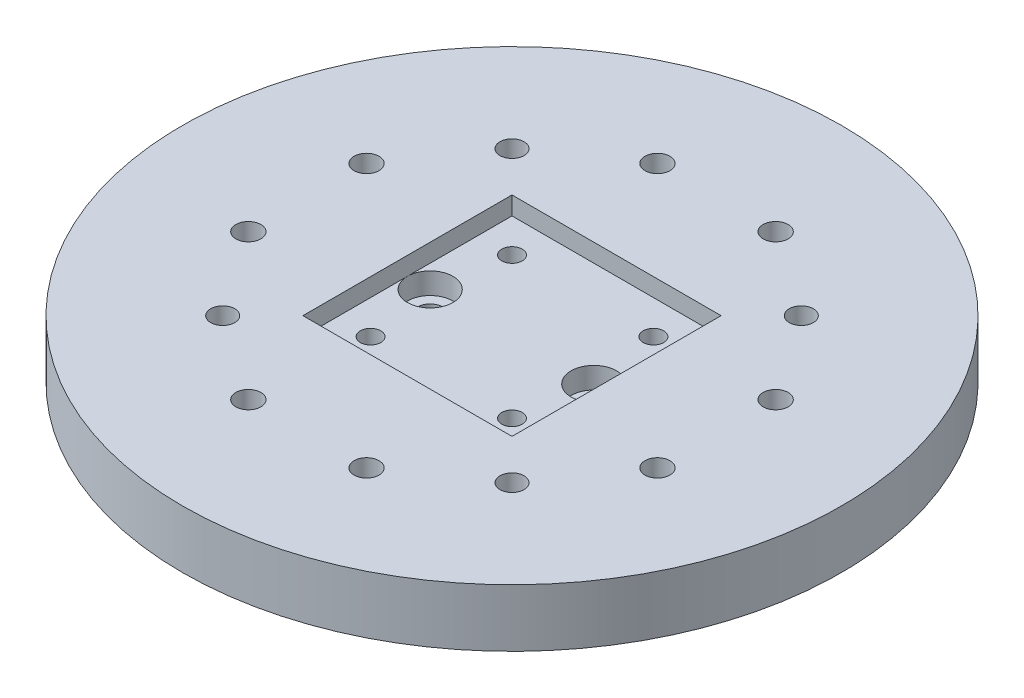
SolidWorks part; units mm, degrees
ref_plane "Front Plane" through (0, 0, 0) normal (0, 0, 1) x (1, 0, 0)
ref_plane "Top Plane" through (0, 0, 0) normal (0, 1, 0) x (1, 0, 0)
ref_plane "Right Plane" through (0, 0, 0) normal (1, 0, 0) x (0, 0, -1)
sketch "Sketch1" plane through (0, 0, 0) normal (0, 1, 0) x (1, 0, 0)
  circle A0 centre (0, 0) radius 72.5
  dimension "D1" = 145
extrude "Boss-Extrude1" add sketch "Sketch1" along normal blind 12.7
sketch "Sketch2" plane through (0, 0, 0) normal (0, -1, 0) x (1, 0, 0)
  line L0 (0, 0) -> (31.8198, 31.8198) construction
  line L1 (0, 72.5) -> (0, -72.5) construction
  line L2 (-31.8198, -31.8198) -> (0, 0) construction
  line L3 (-31.8198, 31.8198) -> (31.8198, -31.8198) construction
  circle A0 centre (0, 0) radius 72.5 construction
  circle A1 centre (31.8198, 31.8198) radius 2.65
  circle A2 centre (31.8198, -31.8198) radius 2.65
  circle A3 centre (-31.8198, -31.8198) radius 2.65
  circle A4 centre (-31.8198, 31.8198) radius 2.65
  dimension "D3" = 5.3
  dimension "D1" = 45
  dimension "D2" = 45
  dimension "D4" = 4
extrude "Cut-Extrude1" cut sketch "Sketch2" against normal through all
sketch "Sketch3" plane through (0, 0, 0) normal (0, -1, 0) x (1, 0, 0)
  circle A0 centre (-31.8198, 31.8198) radius 5
  circle A1 centre (31.8198, 31.8198) radius 5
  circle A2 centre (31.8198, -31.8198) radius 5
  circle A3 centre (-31.8198, -31.8198) radius 5
  circle A4 centre (31.8198, -31.8198) radius 2.65 construction
  dimension "D1" = 10
  dimension "D2" = 4
extrude "Cut-Extrude2" cut sketch "Sketch3" against normal blind 5
sketch "Sketch4" plane through (0, 0, 0) normal (0, -1, 0) x (1, 0, 0)
  line L0 (0, 0) -> (0, 45) construction
  line L1 (0, 0) -> (0, -45) construction
  circle A0 centre (13, 45) radius 2.75
  circle A1 centre (-13, 45) radius 2.75
  circle A2 centre (45, -13) radius 2.75
  circle A3 centre (45, 13) radius 2.75
  circle A4 centre (-13, -45) radius 2.75
  circle A5 centre (13, -45) radius 2.75
  circle A6 centre (-45, 13) radius 2.75
  circle A7 centre (-45, -13) radius 2.75
  dimension "D2" = 5.5
  dimension "D1" = 45
  dimension "D3" = 13
  dimension "D4" = 4
extrude "Cut-Extrude3" cut sketch "Sketch4" against normal through all
sketch "Sketch7" plane through (0, 12.7, 0) normal (0, 1, 0) x (1, 0, 0)
  line L1 (-23, 23) -> (23, 23)
  line L2 (-23, 23) -> (-23, -23)
  line L3 (-23, -23) -> (23, -23)
  line L4 (23, 23) -> (23, -23)
  line L5 (-23, 23) -> (23, -23) construction
  line L6 (-23, -23) -> (23, 23) construction
  point P0 (0, 0)
  dimension "D1" = 46
extrude "Cut-Extrude6" cut sketch "Sketch7" against normal blind 4
sketch "Sketch8" plane through (0, 8.7, 0) normal (0, 1, 0) x (1, 0, 0)
  line L0 (0, 23) -> (0, -23) construction
  line L1 (23, 23) -> (-23, 23) construction
  line L2 (-23, -23) -> (23, -23) construction
  line L3 (-23, 0) -> (23, 0) construction
  line L4 (-23, 23) -> (-23, -23) construction
  line L5 (23, -23) -> (23, 23) construction
  line L6 (0, 0) -> (15.5563, 15.5563) construction
  circle A0 centre (15.5563, 15.5563) radius 2.25
  circle A1 centre (-15.5563, 15.5563) radius 2.25
  circle A2 centre (15.5563, -15.5563) radius 2.25
  circle A3 centre (-15.5563, -15.5563) radius 2.25
  dimension "D3" = 4.5
  dimension "D1" = 22
  dimension "D2" = 45
extrude "Cut-Extrude7" cut sketch "Sketch8" against normal through all
sketch "Sketch9" plane through (0, 0, 0) normal (0, -1, 0) x (1, 0, 0)
  line L0 (0, -6.985) -> (0, 6.985) construction
  circle A0 centre (18, 0) radius 2.75
  circle A1 centre (-18, 0) radius 2.75
  dimension "D1" = 5.5
  dimension "D2" = 18
extrude "Cut-Extrude8" cut sketch "Sketch9" against normal through all
sketch "Sketch10" plane through (0, 8.7, 0) normal (0, 1, 0) x (1, 0, 0)
  line L0 (0, -6.985) -> (0, 6.985) construction
  circle A0 centre (-18, 0) radius 5
  circle A1 centre (18, 0) radius 5
  dimension "D1" = 10
extrude "Cut-Extrude9" cut sketch "Sketch10" against normal offset from surface (4.7 mm away) 4 up to face at (18, 0, -2.75)
